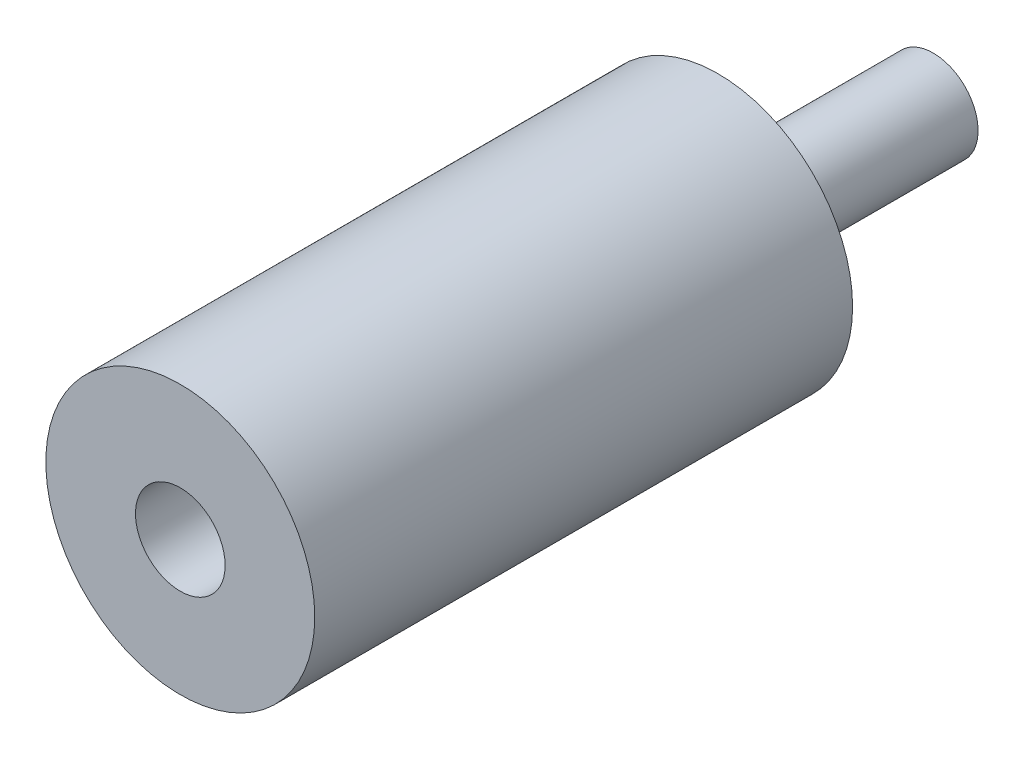
SolidWorks part; units mm, degrees
ref_plane "前视基准面" through (0, 0, 0) normal (0, 0, 1) x (1, 0, 0)
ref_plane "上视基准面" through (0, 0, 0) normal (0, 1, 0) x (1, 0, 0)
ref_plane "右视基准面" through (0, 0, 0) normal (1, 0, 0) x (0, 0, -1)
sketch "草图1" plane through (0, 0, 0) normal (0, 0, 1) x (1, 0, 0)
  circle A0 centre (0, 0) radius 7.5
  dimension "D1" = 15
extrude "凸台-拉伸1" add sketch "草图1" along normal blind 30
sketch "草图2" plane through (0, 0, 0) normal (0, 0, -1) x (-1, 0, 0)
  circle A0 centre (0, 0) radius 2.5
  dimension "D1" = 5
extrude "凸台-拉伸2" add sketch "草图2" along normal blind 12
sketch "草图3" plane through (0, 0, 30) normal (0, 0, 1) x (1, 0, 0)
  circle A0 centre (0, 0) radius 2.5
  dimension "D1" = 5
extrude "切除-拉伸1" cut sketch "草图3" against normal blind 5
